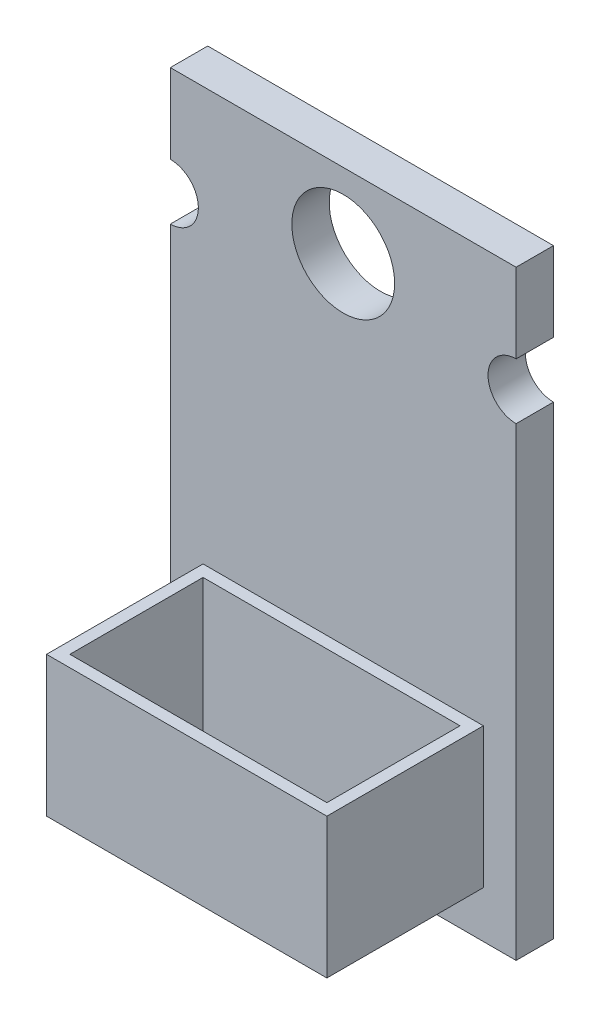
SolidWorks part; units mm, degrees
ref_plane "Alzado" through (0, 0, 0) normal (0, 0, 1) x (1, 0, 0)
ref_plane "Planta" through (0, 0, 0) normal (0, 1, 0) x (1, 0, 0)
ref_plane "Vista lateral" through (0, 0, 0) normal (1, 0, 0) x (0, 0, -1)
sketch "Croquis1" plane through (0, 0, 0) normal (0, 0, 1) x (1, 0, 0)
  line L0 (0, 12.85) -> (0, -12.85) construction
  line L1 (7.4, -12.85) -> (-7.4, -12.85)
  line L2 (7.4, -12.85) -> (7.4, 7.05)
  line L3 (7.4, 12.85) -> (-7.4, 12.85)
  line L4 (-7.4, -12.85) -> (-7.4, 7.05)
  line L5 (7.4, -12.85) -> (-7.4, 12.85) construction
  line L6 (7.4, 12.85) -> (-7.4, -12.85) construction
  line L7 (7.4, 9.45) -> (7.4, 12.85)
  line L8 (-7.4, 12.85) -> (-7.4, 9.45)
  circle A0 centre (0, 9.65) radius 2.2
  arc A1 (-7.4, 7.05) -> (-7.4, 9.45) centre (-7.4, 8.25) ccw
  arc A2 (7.4, 7.05) -> (7.4, 9.45) centre (7.4, 8.25) cw
  point P0 (0, 0)
  dimension "D3" = 4.4
  dimension "D4" = 3.2
  dimension "D5" = 1.2
  dimension "D1" = 14.8
  dimension "D2" = 25.7
  dimension "D6" = 3.4
extrude "Saliente-Extruir1" add sketch "Croquis1" along normal blind 1.6
ref_plane "Plano1" through (0, -10.85, 0) normal (0, -1, 0) x (-1, 0, 0)
sketch "Croquis3" plane through (0, -12.85, 0) normal (0, -1, 0) x (1, 0, 0)
  line L0 (0, 0) -> (0, 4.95) construction
  line L1 (-7.4, 0) -> (7.4, 0) construction
  line L2 (-7.4, 1.6) -> (7.4, 1.6) construction
  line L3 (6, 1.6) -> (-6, 1.6)
  line L4 (6, 1.6) -> (6, 8.3)
  line L5 (6, 8.3) -> (-6, 8.3)
  line L6 (-6, 1.6) -> (-6, 8.3)
  line L7 (6, 1.6) -> (-6, 8.3) construction
  line L8 (6, 8.3) -> (-6, 1.6) construction
  line L9 (5.5, 2.1) -> (5.5, 7.8)
  line L10 (5.5, 7.8) -> (-5.5, 7.8)
  line L11 (-5.5, 2.1) -> (-5.5, 7.8)
  line L12 (5.5, 2.1) -> (-5.5, 2.1)
  dimension "D1" = 12
  dimension "D2" = 6.7
  dimension "D3" = 0.5
extrude "Saliente-Extruir3" add sketch "Croquis3" against normal blind 6 from surface at -2 starting at plane "Plano1"
